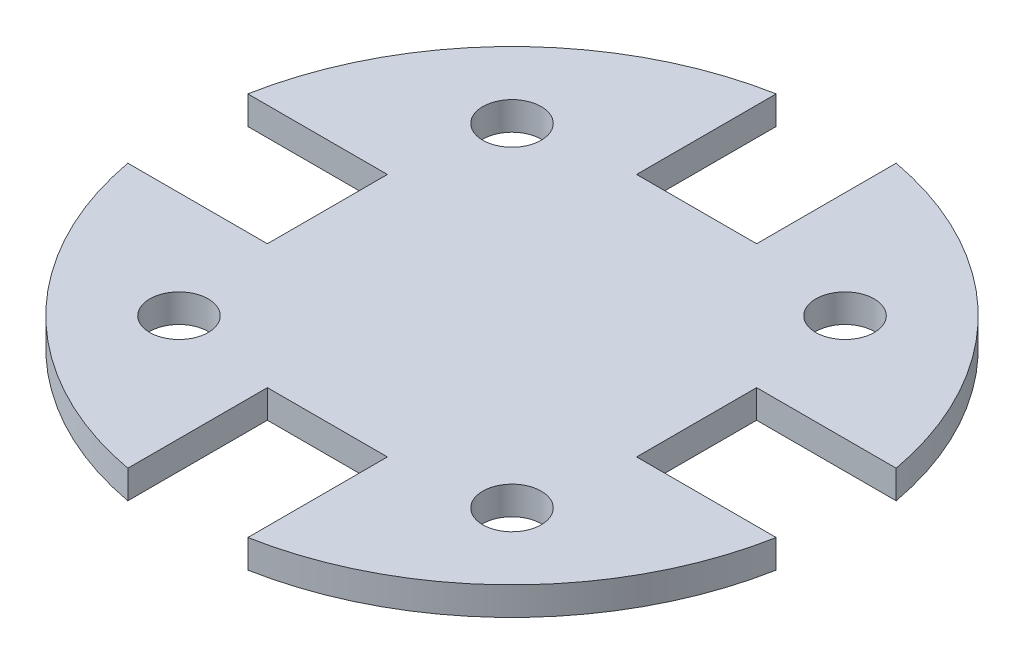
SolidWorks part; units mm, degrees
ref_plane "Front Plane" through (0, 0, 0) normal (0, 0, 1) x (1, 0, 0)
ref_plane "Top Plane" through (0, 0, 0) normal (0, 1, 0) x (1, 0, 0)
ref_plane "Right Plane" through (0, 0, 0) normal (1, 0, 0) x (0, 0, -1)
sketch "Sketch1" plane through (0, 0, 0) normal (0, 1, 0) x (1, 0, 0)
  circle A0 centre (0, 0) radius 35
  dimension "D1" = 70
extrude "Boss-Extrude1" add sketch "Sketch1" along normal blind 5
sketch "Sketch2" plane through (0, 5, 0) normal (0, 1, 0) x (1, 0, 0)
  circle A0 centre (-17.6777, 17.6777) radius 3.1
  circle A1 centre (17.6777, 17.6777) radius 3.1
  circle A2 centre (17.6777, -17.6777) radius 3.1
  circle A3 centre (-17.6777, -17.6777) radius 3.1
  dimension "D1" = 6.2
extrude "Cut-Extrude1" cut sketch "Sketch2" against normal through all
sketch "Sketch3" plane through (0, 5, 0) normal (0, 1, 0) x (1, 0, 0)
  line L0 (-6.17, 30.2) -> (6.17, 30.2) construction
  line L1 (-6.37, 19.6) -> (6.37, 19.6)
  line L2 (-6.37, 19.6) -> (-6.37, 30.4)
  line L3 (-6.37, 30.4) -> (6.37, 30.4)
  line L4 (6.37, 19.6) -> (6.37, 30.4)
  line L5 (-6.37, 19.6) -> (6.37, 30.4) construction
  line L6 (-6.37, 30.4) -> (6.37, 19.6) construction
  line L7 (-6.17, 19.8) -> (-6.17, 30.2) construction
  point P0 (0, 25)
  dimension "D1" = 0.2
  dimension "D2" = 0.2
extrude "Cut-Extrude2" cut sketch "Sketch3" against normal up to vertex (5 mm away)
pattern_circular "CirPattern1" count 4 over 360 about axis through (0, 0, 0) along (0, 1, 0) of "Cut-Extrude2"
sketch "Sketch4" plane through (0, 0, -30.4) normal (0, 0, 1) x (1, 0, 0)
  line L4 (6.37, 5) -> (-6.37, 5)
  line L5 (-6.37, 5) -> (-6.37, 0)
  line L6 (-6.37, 0) -> (6.37, 0)
  line L7 (6.37, 0) -> (6.37, 5)
  line L8 (6.37, 5) -> (-6.37, 5)
  line L9 (-6.37, 5) -> (-6.37, 0)
  line L11 (6.37, 0) -> (6.37, 5)
  line L12 (-6.37, 0) -> (6.37, 0)
  dimension "D1" = 0
extrude "Cut-Extrude3" cut sketch "Sketch4" against normal through all
pattern_circular "CirPattern2" count 4 over 360 about axis through (0, 5, 0) along (0, 1, 0) of "Cut-Extrude3"
sketch "Sketch5" plane through (0, 0, 0) normal (0, -1, 0) x (1, 0, 0)
  line L12 (-19.6, -6.37) -> (-34.4154, -6.37)
  line L13 (-19.6, -6.37) -> (-34.4154, -6.37)
  line L14 (-6.37, -34.4154) -> (-6.37, -19.6)
  line L15 (-6.37, -34.4154) -> (-6.37, -19.6)
  line L16 (-6.37, -19.6) -> (6.37, -19.6)
  line L17 (-6.37, -19.6) -> (6.37, -19.6)
  line L18 (6.37, -19.6) -> (6.37, -34.4154)
  line L19 (6.37, -19.6) -> (6.37, -34.4154)
  line L20 (34.4154, -6.37) -> (19.6, -6.37)
  line L21 (34.4154, -6.37) -> (19.6, -6.37)
  line L22 (19.6, -6.37) -> (19.6, 6.37)
  line L23 (19.6, -6.37) -> (19.6, 6.37)
  line L24 (19.6, 6.37) -> (34.4154, 6.37)
  line L25 (19.6, 6.37) -> (34.4154, 6.37)
  line L26 (6.37, 34.4154) -> (6.37, 19.6)
  line L27 (6.37, 34.4154) -> (6.37, 19.6)
  line L28 (6.37, 19.6) -> (-6.37, 19.6)
  line L29 (6.37, 19.6) -> (-6.37, 19.6)
  line L30 (-6.37, 19.6) -> (-6.37, 34.4154)
  line L31 (-6.37, 19.6) -> (-6.37, 34.4154)
  line L32 (-34.4154, 6.37) -> (-19.6, 6.37)
  line L33 (-34.4154, 6.37) -> (-19.6, 6.37)
  line L34 (-19.6, 6.37) -> (-19.6, -6.37)
  line L35 (-19.6, 6.37) -> (-19.6, -6.37)
  arc A1 (-34.4154, -6.37) -> (-6.37, -34.4154) centre (0, 0) ccw
  arc A6 (-34.4154, -6.37) -> (-6.37, -34.4154) centre (0, 0) ccw
  arc A7 (6.37, -34.4154) -> (34.4154, -6.37) centre (0, 0) ccw
  arc A8 (6.37, -34.4154) -> (34.4154, -6.37) centre (0, 0) ccw
  arc A9 (34.4154, 6.37) -> (6.37, 34.4154) centre (0, 0) ccw
  arc A10 (34.4154, 6.37) -> (6.37, 34.4154) centre (0, 0) ccw
  arc A11 (-6.37, 34.4154) -> (-34.4154, 6.37) centre (0, 0) ccw
  arc A12 (-6.37, 34.4154) -> (-34.4154, 6.37) centre (0, 0) ccw
  dimension "D1" = 0
extrude "Cut-Extrude4" cut sketch "Sketch5" against normal offset from surface (2 mm away) 3 up to face at (0, 5, 0)
